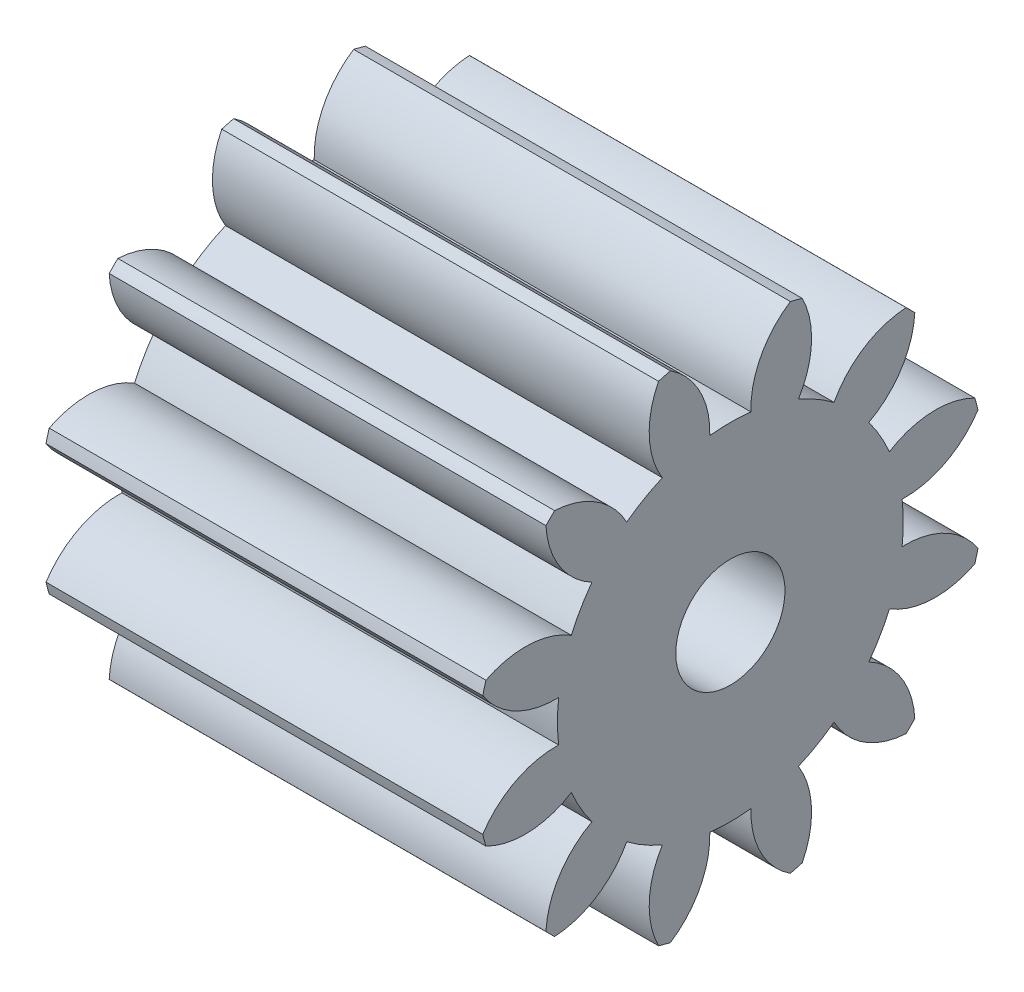
SolidWorks part; units mm, degrees
ref_plane "Plane1" through (0, 0, 0) normal (0, 0, 1) x (1, 0, 0)
ref_plane "Plane2" through (0, 0, 0) normal (0, 1, 0) x (1, 0, 0)
ref_plane "Plane3" through (0, 0, 0) normal (1, 0, 0) x (0, 0, -1)
other "Configuration Table"
sketch "HoldingSke" plane through (0, 0, 0) normal (0, 1, 0) x (1, 0, 0)
  line L0 (0, 0) -> (596.2788, -126.743)
  line L1 (-15, 0) -> (100, 0) construction
  line L2 (0, 0) -> (-2.1039, 2.3779)
  line L3 (0, 0) -> (-11.863, 4.5341)
  line L4 (0, 0) -> (8.4473, 1.7955)
  line L5 (0, 0) -> (-47.5972, -17.7524)
  line L6 (0, 0) -> (-10.5278, -7.1032)
  line L7 (-2.1039, 2.3779) -> (8.8308, 51.9871)
  line L8 (-76.2, 54.61) -> (-72.771, 54.61)
  line L9 (-71.009, 38.7566) -> (-53.1078, 45.2721)
  line L10 (-76.2, 71.12) -> (104.1128, 71.12)
  line L11 (0, 0) -> (-12.7, 0)
  line L12 (-76.2, 101.6) -> (-76.1573, 101.6)
  line L13 (24.9733, 27.94) -> (52.9518, 28.4284)
  line L14 (24.9733, 27.94) -> (25.0241, 27.9398)
  line L15 (24.9733, 27.94) -> (100.4021, 29.52)
  circle A0 centre (0, 0) radius 1.5875
  circle A1 centre (0, 0) radius 5.0292
  circle A2 centre (0, 0) radius 38.1
  circle A3 centre (0, 0) radius 1.5875
  dimension "MHD" = 10.0584
  dimension "Hub_dia" = 76.2
  dimension "Bore" = 3.175
  dimension "MBD" = 3.175
  dimension "Num_teeth" = 12
  dimension "Pitch" = 609.6
  dimension "Overall_len" = 50.8
  dimension "Show_teeth" = 12
  dimension "Thickness" = 12.7
  dimension "OAL" = 50.8001
  dimension "T_dim" = 3.429
  dimension "Ap" = 20
  dimension "H" = 19.05
  dimension "Pitch_radius" = 180.3128
  dimension "Width" = 12.7
  dimension "Backlash" = 0.0427
  dimension "Addendum_fac" = 1
  dimension "Dedendum_fac" = 1.2
  dimension "Clearance_fac" = 0.2
  dimension "Dedendum_add" = 0.0508
sketch "BasProSke" plane through (0, 0, 0) normal (0, 1, 0) x (1, 0, 0)
  line L0 (-10, 0) -> (60, 0) construction
  line L1 (0, 0) -> (0, 7.4083)
  line L2 (0, 0) -> (12.7, 0)
  line L3 (12.7, 0) -> (12.7, 7.4083)
  line L4 (12.7, 7.4083) -> (0, 7.4083)
  dimension "Thickness" = 12.7
  dimension "Diameter" = 14.8167
revolve "Base-Revolve" add sketch "BasProSke" angle 360 about L0
sketch "TooCutSke" plane through (0, 0, 0) normal (1, 0, 0) x (0, 0, -1)
  line L1 (0, 0) -> (0, 107) construction
  line L2 (0, 0) -> (-0.9034, 6.2854) construction
  line L3 (0, 0) -> (-3.2637, 12.1804) construction
  line L4 (-0.9034, 6.2854) -> (-1.6319, 6.0902) construction
  arc A0 (0.5983, 4.9935) -> (-0.5983, 4.9935) centre (0, 0) ccw
  arc A1 (1.7736, 7.219) -> (-1.7736, 7.219) centre (0, 0) ccw
  circle A2 centre (0, 0) radius 6.35 construction
  circle A3 centre (0, 0) radius 5.967 construction
  arc A4 (-0.5983, 4.9935) -> (-1.7736, 7.219) centre (-3.137, 5.0759) ccw
  arc A5 (1.7736, 7.219) -> (0.5983, 4.9935) centre (3.137, 5.0759) ccw
  dimension "Root_dia" = 10.0584
  dimension "Overcut_dia" = 14.8675
  dimension "Pitch_dia" = 12.7
  dimension "Base_dia" = 11.9341
  dimension "Flank_rad" = 2.54
  dimension "Half_ang" = 15
  dimension "Half_CT" = 0.7542
extrude "ToothCut" cut sketch "TooCutSke" along normal through all
fillet "Breaks" [suppressed] radius 0.0212
fillet "RootFillets" [suppressed] radius 0.2625
pattern_circular "TeethCuts" count 12 every 30 about axis through (-10, 0, 0) along (1, 0, 0) of "ToothCut", "RootFillets", "Breaks"
sketch "HubNeaOneSke" plane through (0, 0, 0) normal (-1, 0, 0) x (0, 0, 1)
  circle A0 centre (0, 0) radius 5.0292
  dimension "Diameter" = 10.0584
extrude "HubNearOne" [suppressed] add sketch "HubNeaOneSke" along normal blind 38.1001
sketch "HubNeaBotSke" plane through (0, 0, 0) normal (-1, 0, 0) x (0, 0, 1)
  circle A0 centre (0, 0) radius 5.0292
  dimension "Diameter" = 10.0584
extrude "HubNearBoth" [suppressed] add sketch "HubNeaBotSke" along normal blind 19.05
ref_plane "FarPln" through (12.7, 0, 0) normal (1, 0, 0) x (0, 0, -1)
sketch "HubFarSke" plane through (12.7, 0, 0) normal (1, 0, 0) x (0, 0, -1)
  circle A0 centre (0, 0) radius 5.0292
  dimension "Diameter" = 10.0584
extrude "HubFar" [suppressed] add sketch "HubFarSke" along normal blind 19.05
sketch "BorSke" plane through (0, 0, 0) normal (1, 0, 0) x (0, 0, -1)
  circle A0 centre (0, 0) radius 1.5875
  dimension "Diameter" = 3.175
extrude "Bore" cut sketch "BorSke" along normal mid plane 101.6001
sketch "KeySke" plane through (0, 0, 0) normal (1, 0, 0) x (0, 0, -1)
  line L0 (-0.127, 0) -> (-0.127, 1.8415)
  line L1 (-0.127, 1.8415) -> (0.127, 1.8415)
  line L2 (0.127, 1.8415) -> (0.127, 0)
  line L3 (0, 0) -> (0, 34) construction
  line L4 (-0.127, 0) -> (0.127, 0)
  dimension "Offset" = 1.8415
  dimension "Width" = 0.254
extrude "Keyway" [suppressed] cut sketch "KeySke" along normal mid plane 101.6001
pattern_circular "Keyway2" [suppressed] count 2 every 90 about axis through (-10, 0, 0) along (1, 0, 0)
equation "' \"Pitch@HoldingSke\" = 4"
equation "' \"Num_teeth@HoldingSke\" = 12"
equation "' \"Ap@HoldingSke\" =  20"
equation "' \"Ap@HoldingSke\" = 20"
equation "' \"Width@HoldingSke\" = 0.5"
equation "' \"Hub_dia@HoldingSke\"= 1"
equation "' \"Hub_dia@HoldingSke\" = 1"
equation "' \"Overall_len@HoldingSke\" = 1.0"
equation "' \"Bore@HoldingSke\" = 0.75"
equation "' \"T_dim@HoldingSke\" = 0.85"
equation "' \"Width@KeySke\" = 0.25"
equation "' \"Show_teeth@HoldingSke\" = 13"
equation "' \"Backlash@HoldingSke\" = 0.009"
equation "' \"Addendum_fac@HoldingSke\" = 1.0"
equation "' \"Dedendum_fac@HoldingSke\" = 1.25"
equation "' \"Dedendum_add@HoldingSke\" = 0.00005"
equation "' \"Clearance_fac@HoldingSke\" = 0.25"
equation "' \"Pitch@HoldingSke\" = 0.5"
equation "' \"Num_teeth@HoldingSke\" = 23"
equation "' \"Show_teeth@HoldingSke\" = 23"
equation "' \"Backlash@HoldingSke\" = 0.0375"
equation "\"Overcut_dia@TooCutSke\" = (\"Num_teeth@HoldingSke\" + 2 * \"Addendum_fac@HoldingSke\") / \"Pitch@HoldingSke\" + 0.002"
equation "\"Pitch_dia@TooCutSke\" = \"Num_teeth@HoldingSke\" / \"Pitch@HoldingSke\""
equation "\"Base_dia@TooCutSke\" = \"Num_teeth@HoldingSke\" / \"Pitch@HoldingSke\" * cos((\"Ap@HoldingSke\"  * 3.14159265 / 180))"
equation "\"Root_dia@TooCutSke\" = (\"Num_teeth@HoldingSke\" + 2) / \"Pitch@HoldingSke\" - 2 * (\"Addendum_fac@HoldingSke\" + \"Dedendum_fac@HoldingSke\") / \"Pitch@HoldingSke\" - \"Dedendum_add@HoldingSke\" * 2"
equation "\"Half_ang@TooCutSke\" = 180 / \"Num_teeth@HoldingSke\""
equation "\"Half_CT@TooCutSke\" = \"Num_teeth@HoldingSke\" / \"Pitch@HoldingSke\" * sin((3.14159265 / 2 / \"Num_teeth@HoldingSke\")) / 2 - 7 * \"Backlash@HoldingSke\" / 4"
equation "\"Flank_rad@TooCutSke\" = \"Num_teeth@HoldingSke\" / \"Pitch@HoldingSke\" / 5"
equation "\"Radius@RootFillets\" = \"Clearance_fac@HoldingSke\" / \"Pitch@HoldingSke\" + \"Dedendum_add@HoldingSke\""
equation "\"Break_rad@Breaks\" = 0.02 / \"Pitch@HoldingSke\""
equation "\"Thickness@HoldingSke\" = \"Width@HoldingSke\""
equation "\"OAL@HoldingSke\" = \"Thickness@HoldingSke\""
equation "\"MHD@HoldingSke\" = (\"Num_teeth@HoldingSke\" + 2) / \"Pitch@HoldingSke\" - 2 * (\"Addendum_fac@HoldingSke\" + \"Dedendum_fac@HoldingSke\")  / \"Pitch@HoldingSke\" - \"Dedendum_add@HoldingSke\" * 2"
equation "\"MBD@HoldingSke\" = (\"Num_teeth@HoldingSke\" + 2) / \"Pitch@HoldingSke\" - 2 * (\"Addendum_fac@HoldingSke\" + \"Dedendum_fac@HoldingSke\")  / \"Pitch@HoldingSke\" - \"Dedendum_add@HoldingSke\" * 2 - 0.002"
equation "\"MHD@HoldingSke\" = ((sgn( \"MHD@HoldingSke\" - \"Hub_dia@HoldingSke\" )-1)*( \"MHD@HoldingSke\" - \"Hub_dia@HoldingSke\" ))/-2+ \"Hub_dia@HoldingSke\""
equation "\"MBD@HoldingSke\" = ((sgn( \"MBD@HoldingSke\" - \"Bore@HoldingSke\" )-1)*( \"MBD@HoldingSke\" - \"Bore@HoldingSke\" ))/-2+ \"Bore@HoldingSke\""
equation "\"OAL@HoldingSke\" = ((sgn( \"OAL@HoldingSke\" - \"Overall_len@HoldingSke\" )+1)*( \"OAL@HoldingSke\" - \"Overall_len@HoldingSke\" ))/2 + \"Overall_len@HoldingSke\" + 0.000002"
equation "\"Num_teeth@TeethCuts\" = int( \"Show_teeth@HoldingSke\" ) + 1"
equation "\"Num_teeth@TeethCuts\" = ((sgn( \"Num_teeth@TeethCuts\" - \"Num_teeth@HoldingSke\" )-1)*( \"Num_teeth@TeethCuts\" - \"Num_teeth@HoldingSke\" ))/-2+ \"Num_teeth@HoldingSke\""
equation "\"Num_teeth@TeethCuts\" = ((sgn( \"Num_teeth@TeethCuts\" - 2.0)+1)*( \"Num_teeth@TeethCuts\" - 2.0))/2 +2.0"
equation "\"Angle@TeethCuts\" = 360.0 / \"Num_teeth@HoldingSke\""
equation "\"Diameter@BasProSke\" = (\"Num_teeth@HoldingSke\" + 2 * \"Addendum_fac@HoldingSke\") / \"Pitch@HoldingSke\""
equation "\"Thickness@BasProSke\"  = \"Thickness@HoldingSke\""
equation "' \"Fillet_rad@BasProSke\" =  \"Thickness@HoldingSke\" * 0.05"
equation "' \"Fillet_rad@BasProSke\" = \"Thickness@HoldingSke\" * 0.05"
equation "\"MHD@HoldingSke\" = ((sgn( \"MHD@HoldingSke\" - \"Root_dia@TooCutSke\" )-1)*( \"MHD@HoldingSke\" - \"Root_dia@TooCutSke\" ))/-2+ \"Root_dia@TooCutSke\""
equation "\"Diameter@HubNeaOneSke\" = \"MHD@HoldingSke\""
equation "\"Length@HubNearOne\" = \"OAL@HoldingSke\" - \"Thickness@BasProSke\""
equation "\"Diameter@HubNeaBotSke\" = \"MHD@HoldingSke\""
equation "\"Length@HubNearBoth\" = ( \"OAL@HoldingSke\" - \"Thickness@BasProSke\" ) / 2.0"
equation "\"Thickness@FarPln\" = \"Thickness@BasProSke\""
equation "\"Diameter@HubFarSke\" = \"MHD@HoldingSke\""
equation "\"Length@HubFar\" = ( \"OAL@HoldingSke\" - \"Thickness@BasProSke\" ) / 2.0"
equation "\"Diameter@BorSke\" = \"MBD@HoldingSke\""
equation "\"D1@Bore\" = \"OAL@HoldingSke\" * 2.0"
equation "\"D1@Keyway\" = \"OAL@HoldingSke\" * 2.0"
equation "\"Offset@KeySke\" = \"T_dim@HoldingSke\" - \"MBD@HoldingSke\" / 2.0"
